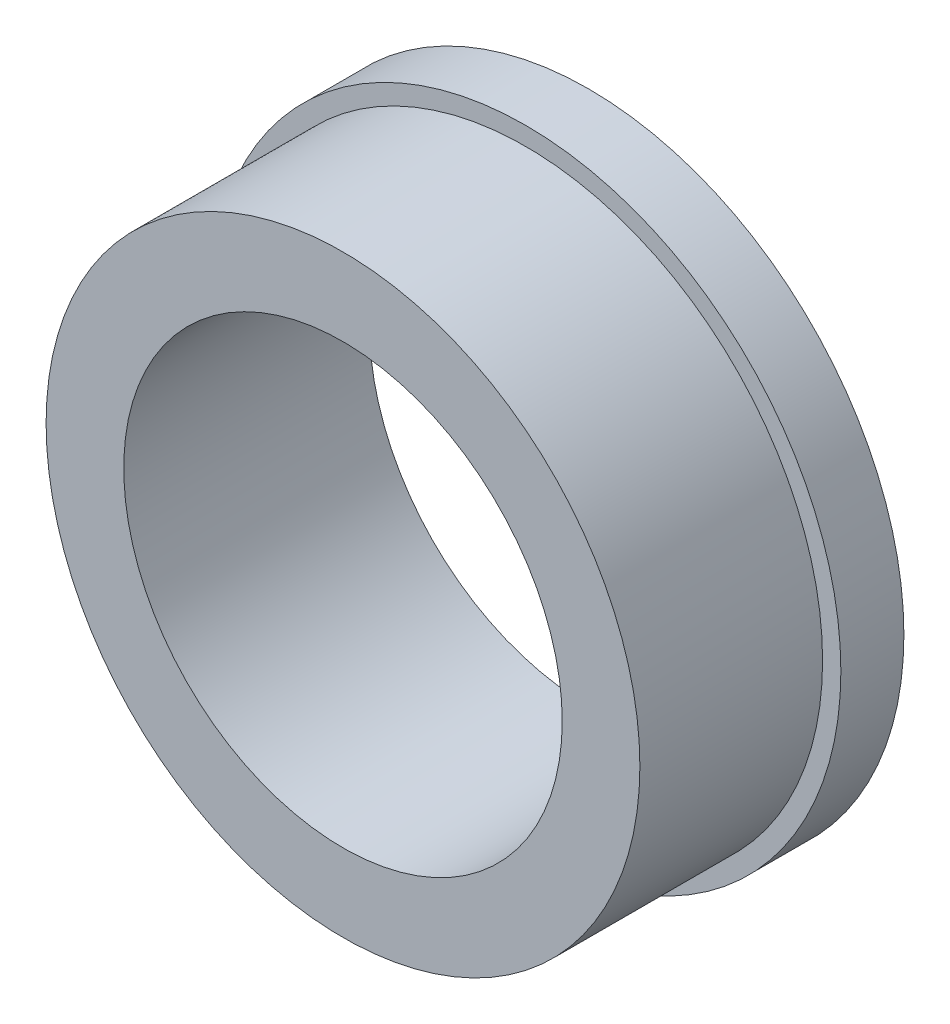
SolidWorks part; units mm, degrees
ref_plane "Alzado" through (0, 0, 0) normal (0, 0, 1) x (1, 0, 0)
ref_plane "Planta" through (0, 0, 0) normal (0, 1, 0) x (1, 0, 0)
ref_plane "Vista lateral" through (0, 0, 0) normal (1, 0, 0) x (0, 0, -1)
sketch "Croquis1" plane through (0, 0, 0) normal (0, 0, 1) x (1, 0, 0)
  circle A0 centre (0, 0) radius 6.9
  dimension "D1" = 13.8
extrude "Saliente-Extruir3" add sketch "Croquis1" along normal blind 5.38
sketch "Croquis4" plane through (0, 0, 5.38) normal (0, 0, 1) x (1, 0, 0)
  line L0 (6.9, 0) -> (5.09, 0) construction
  circle A0 centre (0, 0) radius 6.5
  circle A1 centre (0, 0) radius 6.9 construction
  dimension "D1" = 13
  dimension "D2" = 1.81
extrude "Cortar-Extruir2" cut sketch "Croquis4" against normal blind 4 flip side to cut
sketch "Croquis5" plane through (0, 0, 5.38) normal (0, 0, 1) x (1, 0, 0)
  circle A0 centre (0, 0) radius 4.8
  dimension "D1" = 9.6
extrude "Cortar-Extruir3" cut sketch "Croquis5" against normal up to next
